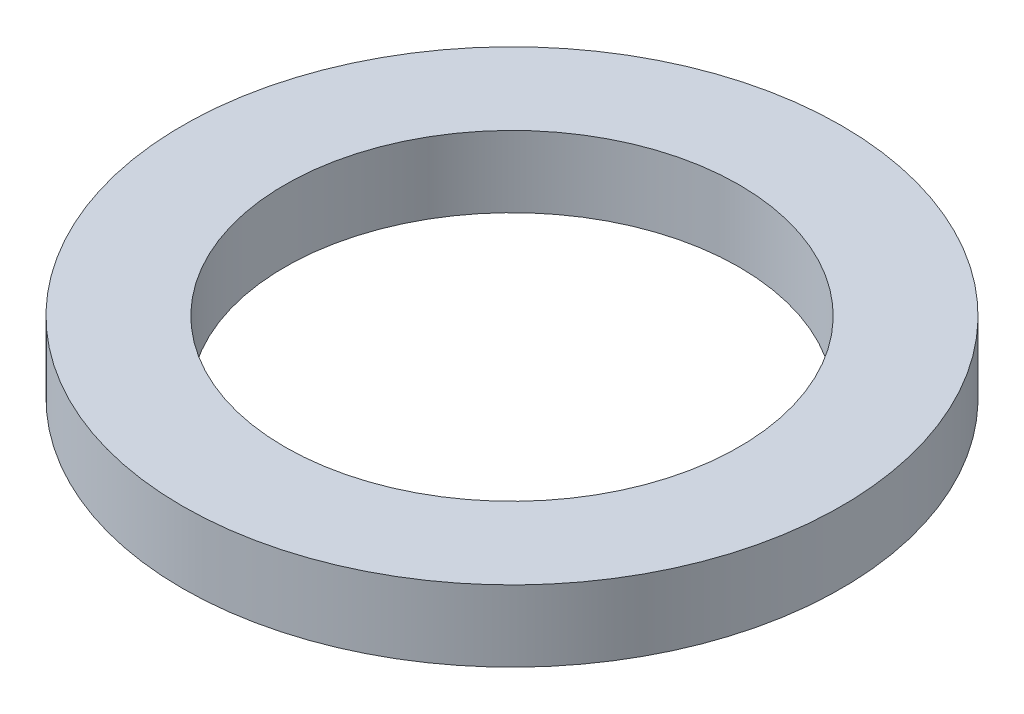
SolidWorks part; units mm, degrees
ref_plane "Front Plane" through (0, 0, 0) normal (0, 0, 1) x (1, 0, 0)
ref_plane "Top Plane" through (0, 0, 0) normal (0, 1, 0) x (1, 0, 0)
ref_plane "Right Plane" through (0, 0, 0) normal (1, 0, 0) x (0, 0, -1)
sketch "Sketch1" plane through (0, 0, 0) normal (0, 1, 0) x (1, 0, 0)
  circle A0 centre (0, 0) radius 12.75
  circle A1 centre (0, 0) radius 18.5
  dimension "D1" = 25.5
  dimension "D2" = 37
extrude "Boss-Extrude1" add sketch "Sketch1" along normal blind 4
